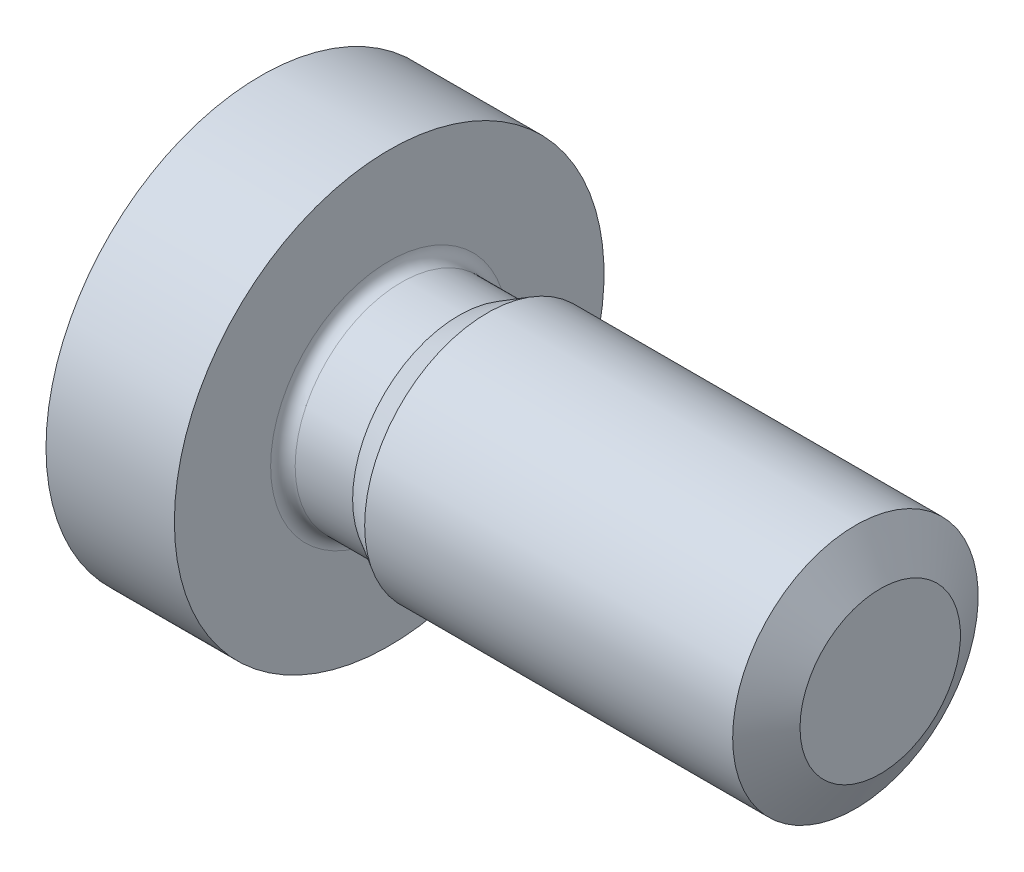
SolidWorks part; units mm, degrees
revolve "基体-旋转" add sketch "草图1" angle 360 about L0
sketch "草图1" plane through (0, 0, 0) normal (0, 0, 1) x (1, 0, 0)
  line L0 (-0.4372, 0) -> (6.983, 0) construction
  line L1 (0, 0) -> (5.4, 0)
  line L2 (5.4, 0) -> (5.4, 1)
  line L3 (5.4, 1) -> (2.2, 1)
  line L4 (2.2, 1) -> (1.9679, 0.866)
  line L5 (1.9679, 0.866) -> (1.4, 0.866)
  line L6 (1.4, 0.866) -> (1.4, 1.75)
  line L7 (1.4, 1.75) -> (0.3542, 1.75)
  arc A0 (0, 0) -> (0.3542, 1.75) centre (4.5, 0) cw
  dimension "D7" = 4.5
  dimension "D1" = 4
  dimension "D2" = 1.4
  dimension "D3" = 3.5
  dimension "D4" = 2
  dimension "D5" = 1.732
  dimension "D6" = 30
  dimension "D8" = 0.8
cosmetic thread "装饰螺纹线1" parameters "D1"=3.2, "D2"=1.732
material "钢"
ref_plane "前视" through (0, 0, 0) normal (0, 0, 1) x (1, 0, 0)
ref_plane "上视" through (0, 0, 0) normal (0, 1, 0) x (1, 0, 0)
ref_plane "右视" through (0, 0, 0) normal (1, 0, 0) x (0, 0, -1)
sketch "尺寸草图" plane through (0, 0, 0) normal (0, 0, 1) x (1, 0, 0)
  line L0 (0, 0) -> (4, 0)
  line L1 (0, 0) -> (0, 3.5)
  line L2 (4, 0) -> (4, 2)
  point P2 (1.4, 0)
  point P6 (4, 0.4)
  point P7 (2.2, 0)
  point P8 (4.5, 0)
  point P9 (0, 2.2)
  point P10 (1.01, 0)
  point P11 (4, 1.9)
  dimension "K" = 1.4
  dimension "l" = 4
  dimension "dk" = 3.5
  dimension "d" = 2
  dimension "P" = 0.4
  dimension "a" = 0.8
  dimension "rf" = 4.5
  dimension "m" = 2.2
  dimension "h" = 1.01
  dimension "r" = 0.1
fillet "圆角1" radius 0.1 1 edges at (1.4, 0, 0.866)
ref_plane "基准面1" through (1.01, 0, 0) normal (1, 0, 0) x (0, 0, -1)
sketch "草图2" plane through (0, 0, 0) normal (1, 0, 0) x (0, 0, -1)
  line L1 (0.2, 1.1) -> (-0.2, 1.1)
  line L2 (0.2, 1.1) -> (0.2, -1.1)
  line L3 (0.2, -1.1) -> (-0.2, -1.1)
  line L4 (-0.2, 1.1) -> (-0.2, -1.1)
  point P4 (0, 1.1)
  point P5 (-0.2, 0)
  dimension "D1" = 2.2
  dimension "D2" = 0.4
sketch "草图3" plane through (1.01, 0, 0) normal (1, 0, 0) x (0, 0, -1)
  point P0 (0, 0)
loft "切除-放样1" cut profiles "草图2", "草图3"
pattern_circular "阵列(圆周)1" count 2 every 90 about axis through (0, 0, 0) along (1, 0, 0) of "切除-放样1"
sketch "草图4" plane through (0, 0, 0) normal (0, 0, 1) x (1, 0, 0)
  line L0 (5.1978, 1) -> (5.5978, 1)
  line L1 (5.5978, 1) -> (5.4, 0.6536)
  line L2 (5.4, 0.6536) -> (5.1978, 1)
  line L3 (4.7747, 0) -> (7.0751, 0) construction
  line L4 (-0.4372, 0) -> (6.983, 0) construction
  line L5 (5.4, -1) -> (5.4, 1) construction
  dimension "D4" = 2
  dimension "D1" = 0.4
  dimension "D2" = 0.3464
  dimension "D3" = 60
revolve "切除-旋转1" cut sketch "草图4" angle 360 about L3
pattern_linear "阵列(线性)1" [suppressed] count 8 spacing 0.4 along (1, 0, 0)
equation "\"D1@草图1\" = \"l@尺寸草图\""
equation "\"D2@草图1\" = \"K@尺寸草图\""
equation "\"D8@草图1\" = \"a@尺寸草图\""
equation "\"D7@草图1\" = \"rf@尺寸草图\""
equation "\"D5@草图1\" = \"d@尺寸草图\"*0.866"
equation "\"D3@草图1\" = \"dk@尺寸草图\""
equation "\"D4@草图1\" = \"d@尺寸草图\""
equation "\"D1@装饰螺纹线1\" = \"l@尺寸草图\"-\"a@尺寸草图\""
equation "\"D2@装饰螺纹线1\" = \"d@尺寸草图\"*0.866"
equation "\"D1@圆角1\" = \"r@尺寸草图\""
equation "\"D1@基准面1\" = \"h@尺寸草图\""
equation "\"D2@草图2\" = \"P@尺寸草图\""
equation "\"D1@草图2\" = \"m@尺寸草图\""
equation "\"D1@草图4\" = \"P@尺寸草图\""
equation "\"D2@草图4\" = \"P@尺寸草图\"*0.866"
equation "\"D4@草图4\" = \"d@尺寸草图\""
equation "\"D3@阵列(线性)1\" = \"P@尺寸草图\""
equation "\"D1@阵列(线性)1\" = (\"l@尺寸草图\"-\"a@尺寸草图\")/\"P@尺寸草图\""
